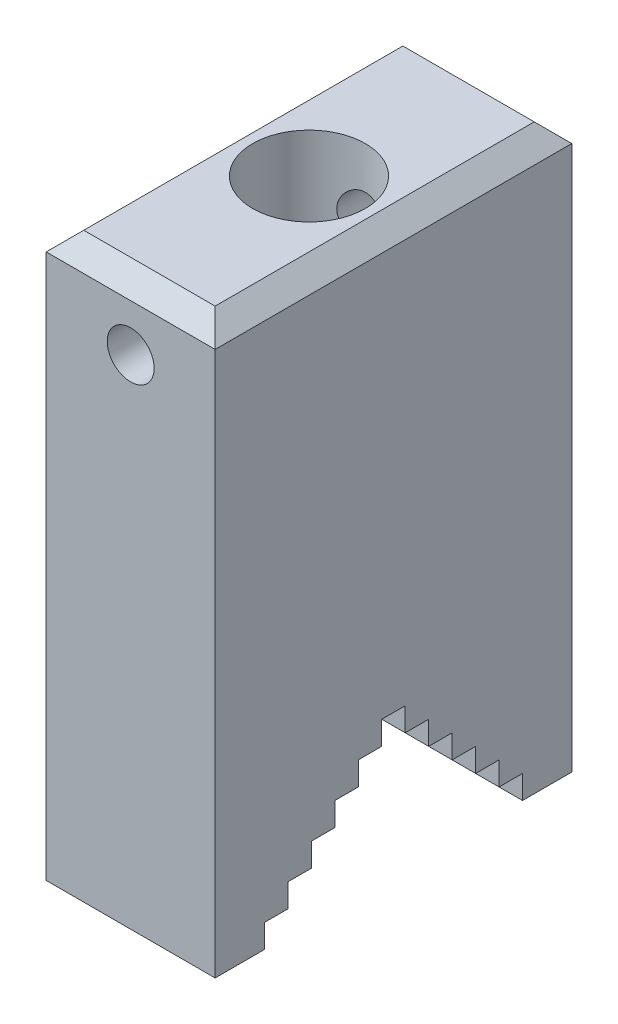
SolidWorks part; units mm, degrees
material "Gray Cast Iron"
ref_plane "Front Plane" through (0, 0, 0) normal (0, 0, 1) x (1, 0, 0)
ref_plane "Top Plane" through (0, 0, 0) normal (0, 1, 0) x (1, 0, 0)
ref_plane "Right Plane" through (0, 0, 0) normal (1, 0, 0) x (0, 0, -1)
sketch "Sketch1" plane through (0, 0, 0) normal (1, 0, 0) x (0, 0, -1)
  line L0 (0, 0) -> (0, 50000) construction
  line L1 (-19, 60) -> (19, 60)
  line L2 (-19, 60) -> (-19, 0)
  line L3 (-19, 0) -> (19, 0)
  line L4 (19, 60) -> (19, 0)
  line L5 (-19, 60) -> (19, 0) construction
  line L6 (-19, 0) -> (19, 60) construction
  line L7 (-13.75, 0) -> (-13.75, 2.5)
  line L8 (-13.75, 2.5) -> (-11.25, 2.5)
  line L9 (-11.25, 2.5) -> (-11.25, 5)
  line L10 (-11.25, 5) -> (-8.75, 5)
  line L11 (-8.75, 5) -> (-8.75, 7.5)
  line L12 (-8.75, 7.5) -> (-6.25, 7.5)
  line L13 (-6.25, 7.5) -> (-6.25, 10)
  line L14 (-6.25, 10) -> (-3.75, 10)
  line L15 (-3.75, 10) -> (-3.75, 12.5)
  line L16 (-3.75, 12.5) -> (-1.25, 12.5)
  line L17 (-1.25, 12.5) -> (-1.25, 15)
  line L18 (1.25, 12.5) -> (1.25, 15)
  line L19 (3.75, 12.5) -> (1.25, 12.5)
  line L20 (3.75, 10) -> (3.75, 12.5)
  line L21 (6.25, 10) -> (3.75, 10)
  line L22 (6.25, 7.5) -> (6.25, 10)
  line L23 (8.75, 7.5) -> (6.25, 7.5)
  line L24 (8.75, 5) -> (8.75, 7.5)
  line L25 (11.25, 5) -> (8.75, 5)
  line L26 (11.25, 2.5) -> (11.25, 5)
  line L27 (13.75, 2.5) -> (11.25, 2.5)
  line L28 (13.75, 0) -> (13.75, 2.5)
  line L29 (-1.25, 15) -> (1.25, 15)
  point P0 (0, 30)
  point P5 (0, 0)
  dimension "D1" = 38
  dimension "D2" = 60
  dimension "D3" = 2.5
  dimension "D4" = 27.5
extrude "Boss-Extrude1" add sketch "Sketch1" along normal mid plane 18 contours L17 L29 L18 L19 L20 L21 L22 L23 L24 L25 L26 L27 L28 L3 L4 L1 L2 L7 L8 L9 L10 L11 L12 L13 L14 L15 L16
chamfer "Chamfer1" distance 2 angle 45 4 edges at (0, 60, -19) (9, 60, 0) (0, 60, 19) (-9, 60, 0)
hole_wizard "Ø1.0mm Dowel Hole1" positions "Sketch2" profile "Sketch3" hole size "Ø1.0" standard "ANSI Metric"
sketch "Sketch2" plane through (0, 60, 0) normal (0, 1, 0) x (1, 0, 0)
  point P0 (0, 0)
sketch "Sketch3" plane through (0, 60, 0) normal (1, 0, 0) x (0, 0, 1)
  line L0 (0, 0) -> (0, 21.4641)
  line L1 (0, 21.4641) -> (6, 18)
  line L2 (6, 18) -> (6, 0)
  line L5 (6, 0) -> (0, 0)
  line L10 (0, 21.4641) -> (-6, 18) construction
  line L11 (0, -6.35) -> (0, 107.95) construction
  dimension "Hole Dia." = 12
  dimension "Hole Depth" = 18
  dimension "Drill Angle" = 120
hole_wizard "M6x1.0 Tapped Hole1" positions "Sketch4" profile "Sketch5" tap size "M6x1.0" standard "ANSI Metric" end condition through all
sketch "Sketch4" plane through (0, 0, 19) normal (0, 0, 1) x (1, 0, 0)
  line L0 (-7, 60) -> (7, 60) construction
  point P0 (0, 53)
  dimension "D1" = 7
sketch "Sketch5" plane through (0, 53, 19) normal (1, 0, 0) x (0, -1, 0)
  line L0 (0, 0) -> (0, 38)
  line L1 (0, 38) -> (2.5, 38)
  line L2 (2.5, 38) -> (2.5, 0)
  line L5 (2.5, 0) -> (0, 0)
  line L11 (0, -6.35) -> (0, 107.95) construction
  dimension "Thru Tap Drill Dia." = 5
  dimension "Thru Tap Drill Depth" = 38
cosmetic thread "Hole Thread1" parameters "D2"=6
